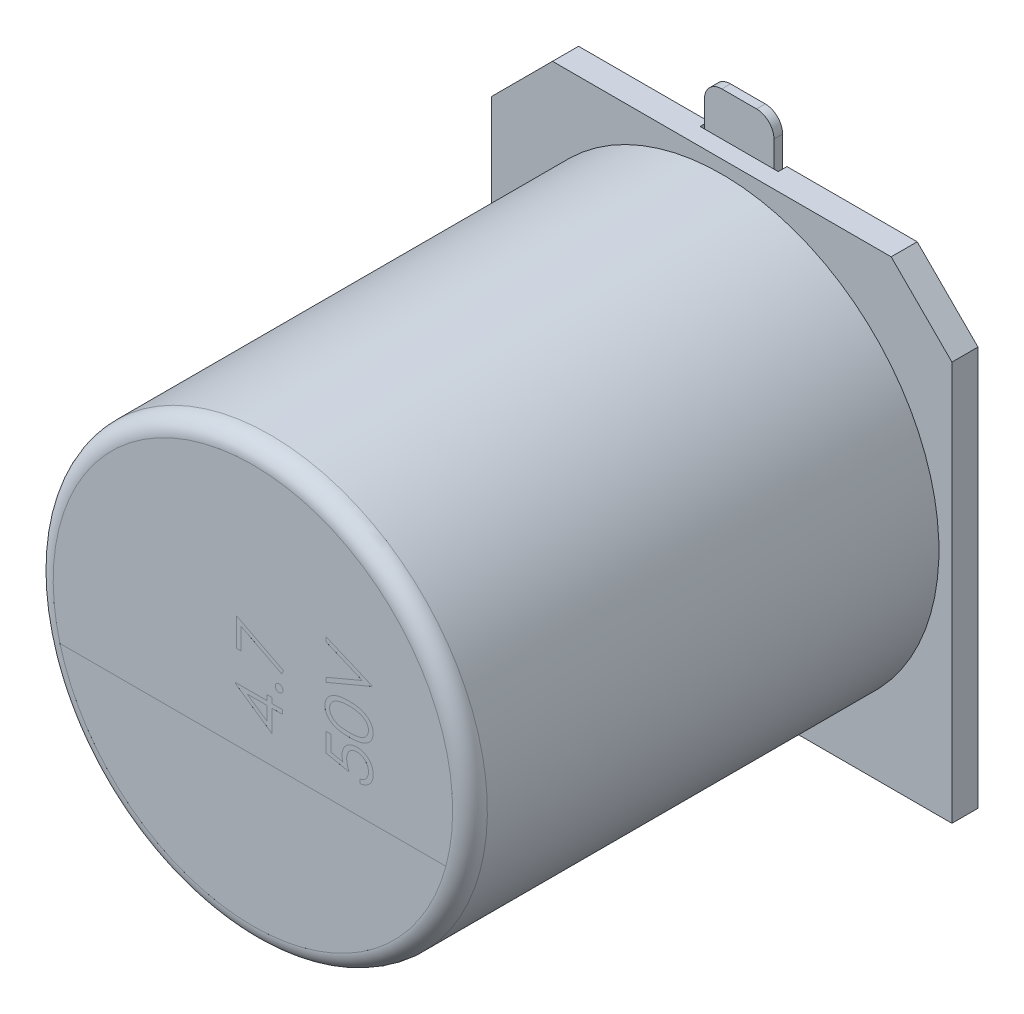
SolidWorks part; units mm, degrees
ref_plane "Frontal" through (0, 0, 0) normal (0, 0, 1) x (1, 0, 0)
ref_plane "Superior" through (0, 0, 0) normal (0, 1, 0) x (1, 0, 0)
ref_plane "Direito" through (0, 0, 0) normal (1, 0, 0) x (0, 0, -1)
sketch "Esboço1" plane through (0, 0, 0) normal (0, 0, 1) x (1, 0, 0)
  line L0 (-2.65, 1.95) -> (-1.95, 2.65)
  line L1 (-1.95, 2.65) -> (1.95, 2.65)
  line L2 (-2.65, 1.95) -> (-2.65, -2.65)
  line L3 (-2.65, -2.65) -> (2.65, -2.65)
  line L4 (2.65, 1.95) -> (2.65, -2.65)
  line L5 (-2.65, 2.65) -> (2.65, -2.65) construction
  line L6 (-2.65, -2.65) -> (2.65, 2.65) construction
  line L7 (1.95, 2.65) -> (2.65, 1.95)
  point P0 (0, 0)
  dimension "D1" = 5.3
  dimension "D2" = 5.3
extrude "Ressalto-extrusão1" add sketch "Esboço1" along normal blind 0.3
sketch "Esboço2" plane through (0, 0, 0.3) normal (0, 0, 1) x (1, 0, 0)
  circle A0 centre (0, 0) radius 2.5
  dimension "D1" = 5
extrude "Ressalto-extrusão2" add sketch "Esboço2" along normal blind 5.4 separate body
fillet "Filete1" radius 0.2 1 edges at (2.5, 0, 5.7)
sketch "Esboço3" plane through (0, 0, 5.7) normal (0, 0, 1) x (1, 0, 0)
  line L0 (-2.2225, -0.5922) -> (2.2225, -0.5922)
  circle A0 centre (0, 0) radius 2.3 construction
  arc A1 (-2.2225, -0.5922) -> (2.2225, -0.5922) centre (0, 0) ccw
extrude "Corte-extrusão1" cut sketch "Esboço3" against normal blind 0.0001
sketch "Esboço4" plane through (0, 0, 5.7) normal (0, 0, 1) x (1, 0, 0)
  line L0 (0.3394, -0.2891) -> (0.3394, 1.9526) construction
  line L1 (1.3716, -0.2891) -> (1.3716, 2.0724) construction
  text T0 "4.7" font "Century Gothic" height in points 2
  text T1 "50V" font "Century Gothic" height in points 2
extrude "Corte-extrusão2" cut sketch "Esboço4" against normal blind 0.0001
sketch "Esboço5" plane through (0, 0, 0) normal (0, 0, -1) x (-1, 0, 0)
  line L0 (0, 2.1) -> (0, 0) construction
  line L1 (-0.45, 3.15) -> (0.45, 3.15)
  line L2 (-0.45, 3.15) -> (-0.45, 1.05)
  line L3 (-0.45, 1.05) -> (0.45, 1.05)
  line L4 (0.45, 3.15) -> (0.45, 1.05)
  line L5 (-0.45, 3.15) -> (0.45, 1.05) construction
  line L6 (-0.45, 1.05) -> (0.45, 3.15) construction
  line L7 (-1.95, 2.65) -> (1.95, 2.65) construction
  line L8 (0, 0) -> (5.286, 0) construction
  line L9 (-0.45, -1.05) -> (0.45, -1.05)
  line L10 (0.45, -3.15) -> (0.45, -1.05)
  line L11 (-0.45, -3.15) -> (-0.45, -1.05)
  line L12 (-0.45, -3.15) -> (0.45, -3.15)
  point P0 (0, 2.1)
  dimension "D1" = 0.5
  dimension "D2" = 2.1
  dimension "D3" = 0.9
extrude "Corte-extrusão3" cut sketch "Esboço5" against normal blind 0.1
sketch "Esboço6" plane through (0, 0, 0.1) normal (0, 0, -1) x (-1, 0, 0)
  line L0 (-0.45, 1.05) -> (0.45, 1.05) construction
  line L1 (-0.2, 3.15) -> (0.2, 3.15)
  line L2 (-0.4, 2.95) -> (-0.4, 1.05)
  line L3 (-0.4, 1.05) -> (0.4, 1.05)
  line L4 (0.4, 2.95) -> (0.4, 1.05)
  line L5 (-0.4, 3.15) -> (0.4, 1.05) construction
  line L6 (-0.4, 1.05) -> (0.4, 3.15) construction
  line L7 (0, 2.1) -> (0, 0) construction
  line L8 (0.45, 2.65) -> (-0.45, 2.65) construction
  line L9 (0, 0) -> (6.6324, 0) construction
  line L10 (-0.4, -1.05) -> (0.4, -1.05)
  line L11 (-0.4, -2.95) -> (-0.4, -1.05)
  line L12 (0.4, -2.95) -> (0.4, -1.05)
  line L13 (-0.2, -3.15) -> (0.2, -3.15)
  line L14 (-0.45, 1.05) -> (-0.45, 2.65) construction
  arc A0 (0.2, 3.15) -> (0.4, 2.95) centre (0.2, 2.95) cw
  arc A1 (-0.2, 3.15) -> (-0.4, 2.95) centre (-0.2, 2.95) ccw
  arc A2 (0.2, -3.15) -> (0.4, -2.95) centre (0.2, -2.95) ccw
  arc A3 (-0.2, -3.15) -> (-0.4, -2.95) centre (-0.2, -2.95) cw
  point P0 (0, 2.1)
  dimension "D3" = 0.2
  dimension "D1" = 0.05
  dimension "D2" = 0.5
extrude "Ressalto-extrusão3" add sketch "Esboço6" along normal up to surface (0.1 mm away) separate body up to face at (0, 0.2786, 0)
